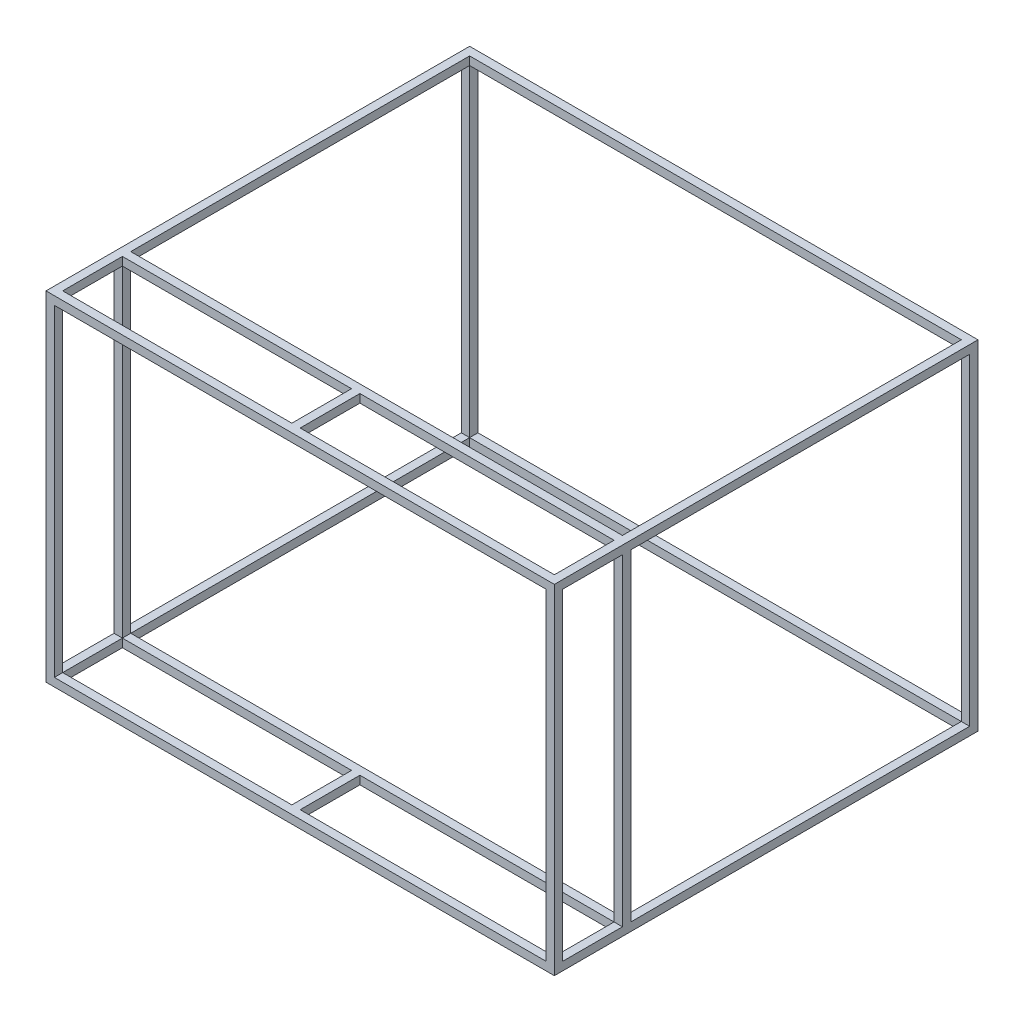
SolidWorks part; units mm, degrees
ref_plane "Front Plane" through (0, 0, 0) normal (0, 0, 1) x (1, 0, 0)
ref_plane "Top Plane" through (0, 0, 0) normal (0, 1, 0) x (1, 0, 0)
ref_plane "Right Plane" through (0, 0, 0) normal (1, 0, 0) x (0, 0, -1)
sketch "Sketch1" plane through (0, 0, 0) normal (0, 0, 1) x (1, 0, 0)
  line L9 (22.3459, 684.9521) -> (936.7459, 684.9521)
  line L10 (22.3459, 684.9521) -> (22.3459, 75.3521)
  line L11 (22.3459, 75.3521) -> (936.7459, 75.3521)
  line L12 (936.7459, 684.9521) -> (936.7459, 75.3521)
  line L13 (37.3459, 669.9521) -> (921.7459, 669.9521)
  line L14 (37.3459, 669.9521) -> (37.3459, 90.3521)
  line L15 (37.3459, 90.3521) -> (921.7459, 90.3521)
  line L16 (921.7459, 669.9521) -> (921.7459, 90.3521)
  dimension "D1" = 914.4
  dimension "D2" = 609.6
  dimension "D3" = 15
  dimension "D4" = 15
  dimension "D5" = 15
  dimension "D6" = 15
extrude "Boss-Extrude2" add sketch "Sketch1" along normal blind 762
sketch "Sketch4" plane through (0, 75.3521, 0) normal (0, -1, 0) x (-1, 0, 0)
  line L0 (-22.3459, 0) -> (-936.7459, 0) construction
  line L1 (-37.3459, -624.6) -> (-921.7459, -624.6)
  line L2 (-37.3459, -624.6) -> (-37.3459, -15)
  line L3 (-37.3459, -15) -> (-921.7459, -15)
  line L4 (-921.7459, -624.6) -> (-921.7459, -15)
  line L5 (-37.3459, -747) -> (-449.5459, -747)
  line L6 (-37.3459, -747) -> (-37.3459, -639.6)
  line L7 (-37.3459, -639.6) -> (-449.5459, -639.6)
  line L8 (-449.5459, -747) -> (-449.5459, -639.6)
  line L9 (-464.5459, -747) -> (-921.7459, -747)
  line L10 (-464.5459, -747) -> (-464.5459, -639.6)
  line L11 (-464.5459, -639.6) -> (-921.7459, -639.6)
  line L12 (-921.7459, -747) -> (-921.7459, -639.6)
  line L13 (-22.3459, -762) -> (-22.3459, 0) construction
  line L14 (-936.7459, -762) -> (-936.7459, 0) construction
  point P18 (-449.5459, -693.3)
  dimension "D1" = 15
  dimension "D2" = 15
  dimension "D3" = 15
  dimension "D4" = 609.6
  dimension "D5" = 15
  dimension "D6" = 15
  dimension "D7" = 107.4
  dimension "D8" = 15
  dimension "D9" = 107.4
  dimension "D10" = 15
  dimension "D11" = 412.2
  dimension "D12" = 15
extrude "Cut-Extrude3" cut sketch "Sketch4" against normal blind 762
sketch "Sketch5" plane through (936.7459, 0, 0) normal (1, 0, 0) x (0, 0, -1)
  line L0 (-762, 684.9521) -> (0, 684.9521) construction
  line L1 (-747, 90.3521) -> (-639.6, 90.3521)
  line L2 (-747, 90.3521) -> (-747, 669.9521)
  line L3 (-747, 669.9521) -> (-639.6, 669.9521)
  line L4 (-639.6, 90.3521) -> (-639.6, 669.9521)
  line L5 (-624.6, 90.3521) -> (-15, 90.3521)
  line L6 (-624.6, 90.3521) -> (-624.6, 669.9521)
  line L7 (-624.6, 669.9521) -> (-15, 669.9521)
  line L8 (-15, 90.3521) -> (-15, 669.9521)
  line L9 (-762, 75.3521) -> (0, 75.3521) construction
  line L10 (0, 75.3521) -> (0, 684.9521) construction
  dimension "D1" = 15
  dimension "D2" = 15
  dimension "D3" = 15
  dimension "D4" = 15
  dimension "D5" = 15
  dimension "D6" = 15
  dimension "D7" = 15
  dimension "D8" = 609.6
extrude "Cut-Extrude4" cut sketch "Sketch5" against normal through all both and the other way through all
